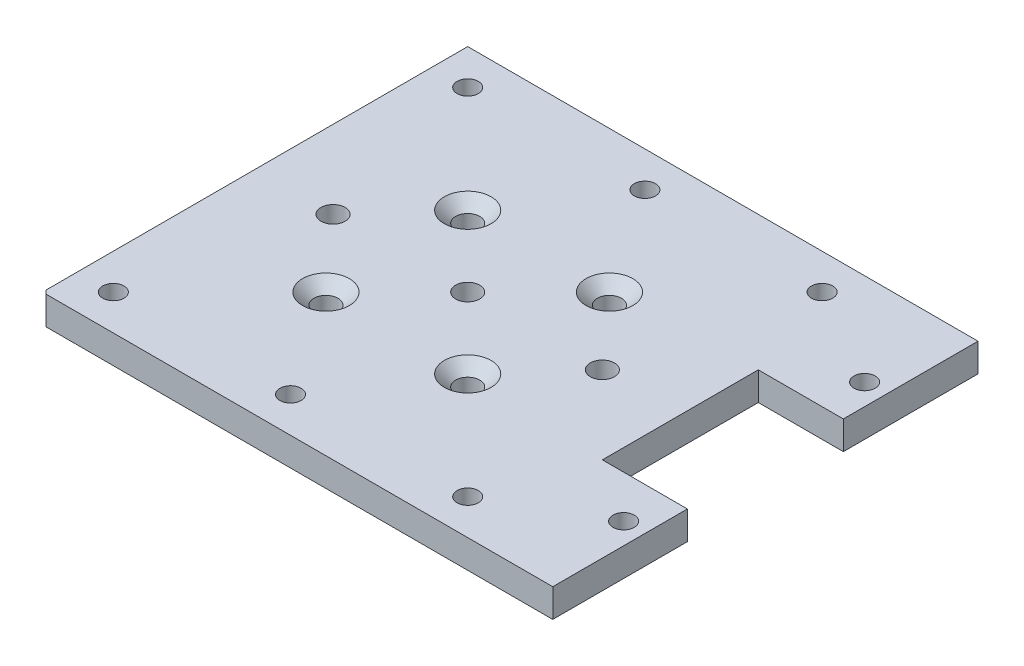
SolidWorks part; units mm, degrees
ref_plane "前视基准面" through (0, 0, 0) normal (0, 0, 1) x (1, 0, 0)
ref_plane "上视基准面" through (0, 0, 0) normal (0, 1, 0) x (1, 0, 0)
ref_plane "右视基准面" through (0, 0, 0) normal (1, 0, 0) x (0, 0, -1)
other "Configuration Table"
sketch "草图1" plane through (0, 0, 0) normal (0, 1, 0) x (1, 0, 0)
  line L1 (-30, -30) -> (30, -30)
  line L2 (-30, -30) -> (-30, 30)
  line L3 (-30, 30) -> (30, 30)
  line L4 (30, -30) -> (30, 30)
  line L5 (-30, -30) -> (30, 30) construction
  line L6 (-30, 30) -> (30, -30) construction
  point P0 (0, 0)
  dimension "D1" = 60
  dimension "D2" = 60
extrude "凸台-拉伸1" add sketch "草图1" along normal blind 4
hole_wizard "M3 十字槽沉头木螺钉的锥形沉头孔1" positions "草图2" profile "草图3" countersink size "M3" standard "GB" end condition through all
sketch "草图2" plane through (0, 4, 0) normal (0, 1, 0) x (1, 0, 0)
  point P6 (-10, 10)
  point P38 (10, 10)
  point P39 (10, -10)
  point P40 (-10, -10)
  dimension "D1" = 10
  dimension "D2" = 10
  dimension "D3" = 4
sketch "草图3" plane through (-10, 4, -10) normal (1, 0, 0) x (0, 0, 1)
  line L0 (0, 0) -> (0, 4)
  line L1 (0, 4) -> (1.7, 4)
  line L2 (1.7, 4) -> (1.7, 1.6)
  line L3 (1.7, 1.6) -> (3.3, 0)
  line L5 (3.3, 0) -> (0, 0)
  line L6 (-1.7, 1.6) -> (-3.3, 0) construction
  line L11 (0, -6.35) -> (0, 107.95) construction
  dimension "通孔孔直径" = 3.4
  dimension "通孔孔深度" = 4
  dimension "近端锥形沉头孔直径" = 6.6
  dimension "近端锥形沉头孔角度" = 90
hole_wizard "M3 十字槽沉头木螺钉的锥形沉头孔2" positions "草图4" profile "草图5" countersink size "M3" standard "GB" end condition through all
sketch "草图4" plane through (0, 0, 0) normal (0, -1, 0) x (-1, 0, 0)
  line L0 (-30, 0) -> (30, 0) construction
  line L1 (-30, -30) -> (-30, 30) construction
  line L2 (30, 30) -> (30, -30) construction
  point P0 (19, 0)
  point P2 (0, 0)
  point P4 (-19, 0)
  dimension "D1" = 19
  dimension "D2" = 19
sketch "草图5" plane through (-19, 0, 0) normal (1, 0, 0) x (0, 0, -1)
  line L0 (0, 0) -> (0, 4)
  line L1 (0, 4) -> (1.7, 4)
  line L2 (1.7, 4) -> (1.7, 1.6)
  line L3 (1.7, 1.6) -> (3.3, 0)
  line L5 (3.3, 0) -> (0, 0)
  line L6 (-1.7, 1.6) -> (-3.3, 0) construction
  line L11 (0, -6.35) -> (0, 107.95) construction
  dimension "通孔孔直径" = 3.4
  dimension "通孔孔深度" = 4
  dimension "近端锥形沉头孔直径" = 6.6
  dimension "近端锥形沉头孔角度" = 90
hole_wizard "孔1" positions "草图6" profile "草图7" legacy end condition through all
sketch "草图6" plane through (0, 4, 0) normal (0, 1, 0) x (1, 0, 0)
  line L0 (30, 30) -> (-30, 30) construction
  line L1 (-30, 30) -> (-30, -30) construction
  line L3 (-30, -30) -> (30, -30) construction
  line L5 (0, -30) -> (0, 30) construction
  line L7 (30, -30) -> (30, 30) construction
  point P0 (25, 25)
  point P2 (25, -25)
  point P4 (0, -25)
  point P6 (-25, -25)
  point P8 (-25, 25)
  point P12 (0, 25)
  dimension "D1" = 5
  dimension "D2" = 5
  dimension "D3" = 5
  dimension "D4" = 5
  dimension "D5" = 5
  dimension "D6" = 5
  dimension "D7" = 5
  dimension "D8" = 5
  dimension "D9" = 5
  dimension "D10" = 5
sketch "草图7" plane through (25, 4, -25) normal (1, 0, 0) x (0, 0, 1)
  line L0 (0, 0) -> (0, 4)
  line L1 (0, 4) -> (1.5, 4)
  line L2 (1.5, 4) -> (1.5, 0)
  line L3 (1.5, 0) -> (0, 0)
  line L4 (0, 110) -> (0, -10) construction
  dimension "直径" = 3
  dimension "深度" = 4
sketch "草图9" plane through (0, 4, 0) normal (0, 1, 0) x (1, 0, 0)
  line L1 (30, -30) -> (42, -30)
  line L2 (30, -30) -> (30, -11)
  line L3 (30, -11) -> (42, -11)
  line L4 (42, -30) -> (42, -11)
  circle A0 centre (39, -17) radius 1.5
  dimension "D3" = 3
  dimension "D1" = 19
  dimension "D2" = 12
  dimension "D4" = 13
  dimension "D5" = 3
extrude "凸台-拉伸3" add sketch "草图9" against normal up to surface (4 mm away) up to face at (25, 0, -23.5)
chamfer "倒角1" distance 0.5 angle 45 1 edges at (-30, 2, 30)
ref_plane "基准面2" through (0, 0, 0) normal (0, 0, 1) x (1, 0, 0)
mirror "镜向1" about plane through (0, 0, 0) normal (0, 0, 1) of "凸台-拉伸3"
